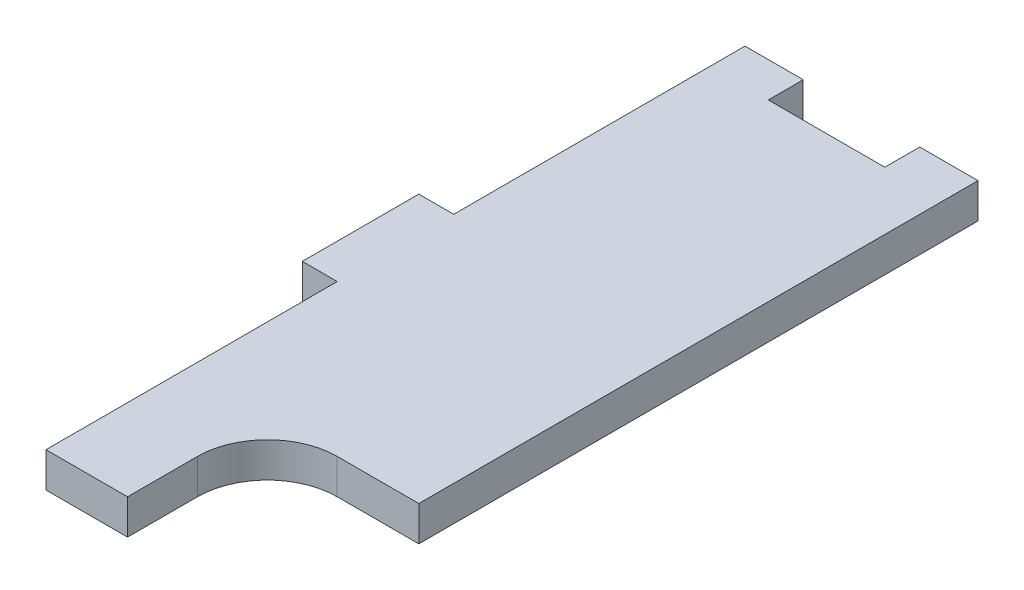
SolidWorks part; units mm, degrees
ref_plane "Front Plane" through (0, 0, 0) normal (0, 0, 1) x (1, 0, 0)
ref_plane "Top Plane" through (0, 0, 0) normal (0, 1, 0) x (1, 0, 0)
ref_plane "Right Plane" through (0, 0, 0) normal (1, 0, 0) x (0, 0, -1)
sketch "Sketch1" plane through (0, 0, 0) normal (0, 1, 0) x (1, 0, 0)
  line L0 (-3, -24) -> (-3, -30)
  line L1 (10, 30) -> (5, 30)
  line L2 (10, 30) -> (10, -18)
  line L3 (-3, -30) -> (-10, -30)
  line L4 (-10, 30) -> (-10, 5)
  line L5 (10, 30) -> (-10, -30) construction
  line L6 (10, -30) -> (-10, 30) construction
  line L7 (3, -18) -> (10, -18)
  line L8 (-10, -5) -> (-10, -30)
  line L9 (-10, 5) -> (-13, 5)
  line L10 (-5, 30) -> (-10, 30)
  line L11 (-10, -5) -> (-13, -5)
  line L12 (-13, 5) -> (-13, -5)
  line L14 (-5, 30) -> (-5, 27)
  line L15 (-5, 27) -> (5, 27)
  line L16 (5, 30) -> (5, 27)
  arc A0 (3, -18) -> (-3, -24) centre (3, -24) ccw
  point P0 (0, 0)
  dimension "D3" = 12
  dimension "D1" = 60
  dimension "D2" = 20
  dimension "D4" = 7
  dimension "D5" = 10
  dimension "D6" = 10
  dimension "D7" = 5
  dimension "D8" = 3
  dimension "D9" = 3
  dimension "D10" = 25
extrude "Boss-Extrude1" add sketch "Sketch1" along normal blind 3
